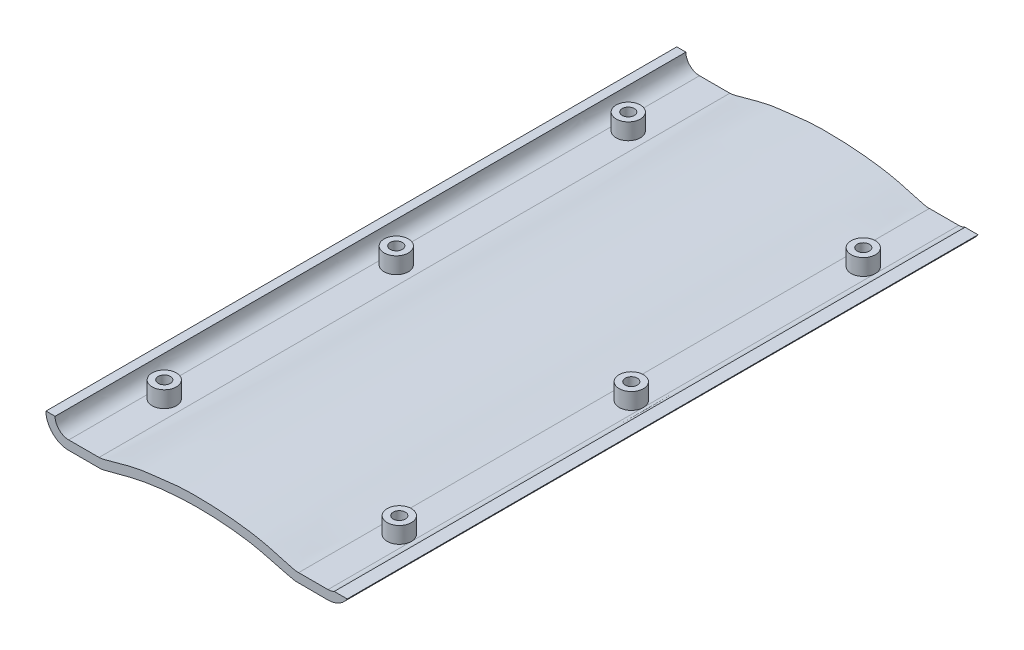
SolidWorks part; units mm, degrees
ref_plane "Front Plane" through (0, 0, 0) normal (0, 0, 1) x (1, 0, 0)
ref_plane "Top Plane" through (0, 0, 0) normal (0, 1, 0) x (1, 0, 0)
ref_plane "Right Plane" through (0, 0, 0) normal (1, 0, 0) x (0, 0, -1)
sketch "Sketch1" plane through (0, 0, 0) normal (0, 0, 1) x (1, 0, 0)
  line L0 (-63.2548, 42.1969) -> (-60.2548, 42.1969)
  line L1 (31.7869, 38.197) -> (36.0693, 38.1969)
  line L2 (18.8515, 34.7479) -> (29.725, 34.6969)
  line L3 (20.0455, 37.6969) -> (29.725, 37.6969)
  line L4 (-55.7548, 37.6969) -> (-45.7548, 37.6969)
  line L5 (-45.7548, 34.6969) -> (-55.7548, 34.6969)
  spline S0 degree 3 poles (-63.2548, 42.1969) (-63.3683, 38.1655) (-59.7512, 34.5968) (-55.7548, 34.6969) knots 0 0 0 0 1 1 1 1
  spline S1 degree 3 poles (-60.2548, 42.1969) (-60.3293, 39.7849) (-58.1427, 37.6333) (-55.7548, 37.6969) knots 0 0 0 0 1 1 1 1
  spline S2 degree 3 poles (-45.7548, 37.6969) (-44.8755, 37.7075) (-42.3864, 38.4334) (-38.0801, 39.595) (-32.1887, 41.1202) (-26.1041, 41.682) (-19.5641, 42.6066) (-11.8101, 42.7406) (-2.2119, 42.2832) (7.9368, 40.8533) (15.2004, 38.7535) (19.0553, 37.6493) (20.0455, 37.6969) knots 0 0 0 0 0.039253 0.115653 0.201009 0.31188 0.389597 0.497603 0.659471 0.82134 0.955956 1 1 1 1
  spline S3 degree 3 poles (-45.7548, 34.6969) (-44.6528, 34.6892) (-41.8389, 35.4463) (-36.7313, 36.8985) (-30.3958, 38.3186) (-22.2737, 39.3548) (-13.0131, 39.8467) (-3.4368, 39.32) (7.29, 37.9925) (14.2379, 35.6752) (18.8515, 34.7479) knots 0 0 0 0 0.050081 0.132344 0.243528 0.346436 0.506688 0.66694 0.784747 1 1 1 1
  spline S4 degree 2 poles (29.725, 34.6969) (33.7985, 34.813) (36.0693, 38.1969) knots 0 0 0 1 1 1
  spline S5 degree 2 poles (29.725, 37.6969) (30.8157, 37.7005) (31.7869, 38.197) knots 0 0 0 1 1 1
extrude "Boss-Extrude1" add sketch "Sketch1" along normal mid plane 208
sketch "Sketch3" plane through (0, 37.6969, 0) normal (0, 1, 0) x (1, 0, 0)
  line L0 (-63.2548, -104) -> (-63.2548, 104) construction
  circle A0 centre (-51.7548, -76.5) radius 4
  circle A1 centre (-51.7548, -76.5) radius 2
  dimension "D2" = 8
  dimension "D3" = 4
  dimension "D1" = 11.5
extrude "Boss-Extrude2" add sketch "Sketch3" along normal blind 5.39 contours A0
pattern_linear "LPattern1" count 2 spacing 77.5 along (1, 0, 0) count 3 spacing 76.5 along (0, 0, -1) of "Boss-Extrude2"
sketch "Sketch4" plane through (0, 43.0869, 0) normal (0, 1, 0) x (1, 0, 0)
  circle A0 centre (-51.7548, -76.5) radius 2
  dimension "D1" = 4
extrude "Cut-Extrude1" cut sketch "Sketch4" against normal blind 20
pattern_linear "LPattern2" count 2 spacing 77.5 along (1, 0, 0) count 3 spacing 76.5 along (0, 0, -1) of "Cut-Extrude1"
